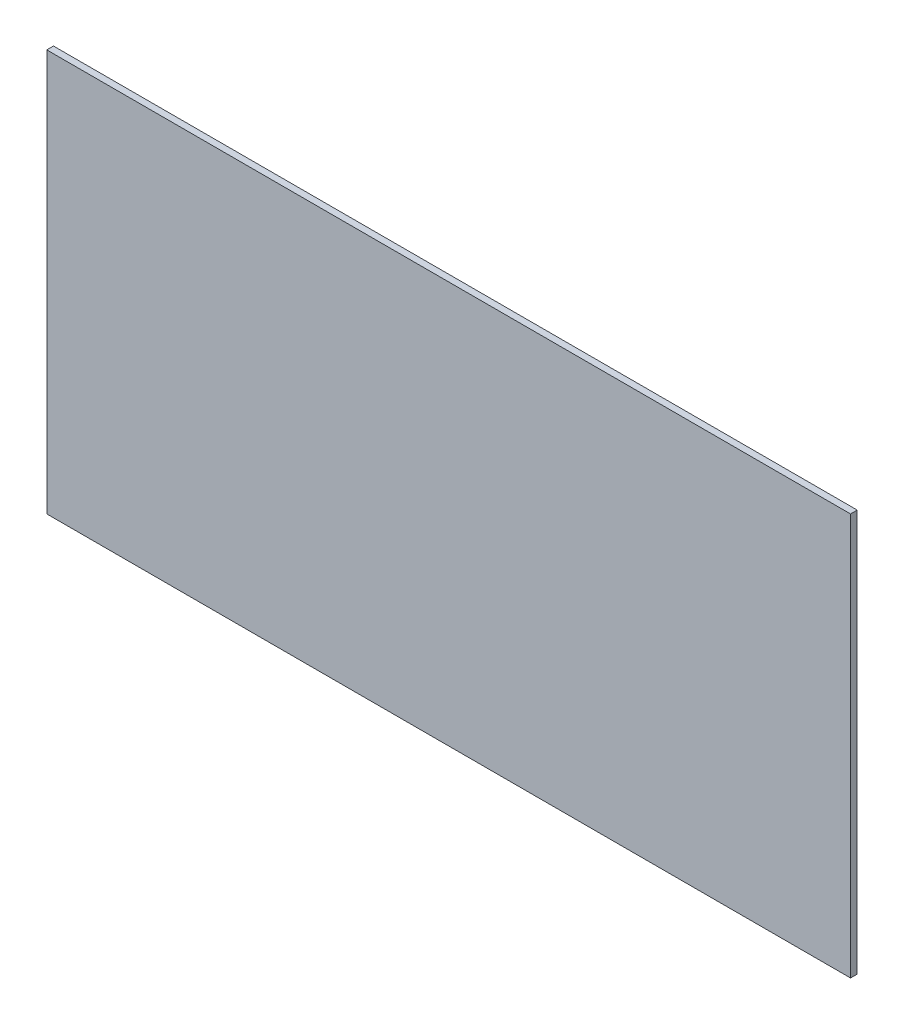
SolidWorks part; units mm, degrees
ref_plane "Front Plane" through (0, 0, 0) normal (0, 0, 1) x (1, 0, 0)
ref_plane "Top Plane" through (0, 0, 0) normal (0, 1, 0) x (1, 0, 0)
ref_plane "Right Plane" through (0, 0, 0) normal (1, 0, 0) x (0, 0, -1)
sketch "Sketch1" plane through (0, 0, 0) normal (0, 0, 1) x (1, 0, 0)
  line L0 (0, 0) -> (0, 152.4)
  line L1 (0, 152.4) -> (304.8, 152.4)
  line L2 (304.8, 152.4) -> (304.8, 0)
  line L3 (304.8, 0) -> (0, 0)
  dimension "D1" = 304.8
  dimension "D2" = 152.4
extrude "Boss-Extrude1" add sketch "Sketch1" along normal blind 2.54
